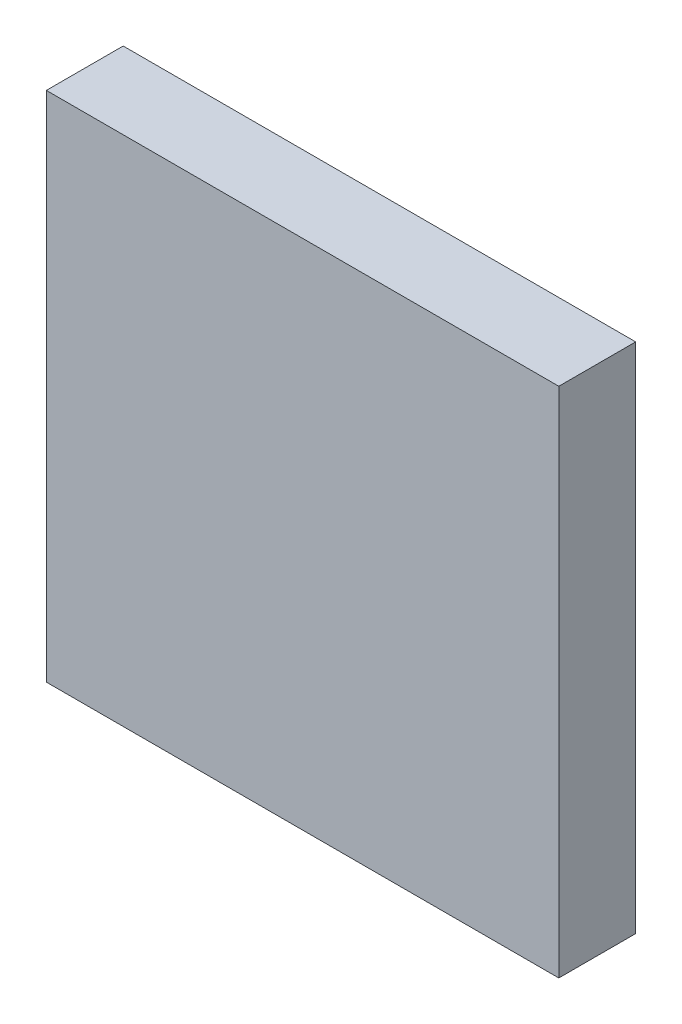
SolidWorks part; units mm, degrees
ref_plane "前视基准面" through (0, 0, 0) normal (0, 0, 1) x (1, 0, 0)
ref_plane "上视基准面" through (0, 0, 0) normal (0, 1, 0) x (1, 0, 0)
ref_plane "右视基准面" through (0, 0, 0) normal (1, 0, 0) x (0, 0, -1)
sketch "草图1" plane through (0, 0, 0) normal (0, 0, 1) x (1, 0, 0)
  line L1 (0, 0) -> (40, 0)
  line L2 (0, 0) -> (0, 40)
  line L3 (0, 40) -> (40, 40)
  line L4 (40, 0) -> (40, 40)
  dimension "D1" = 40
  dimension "D2" = 40
extrude "凸台-拉伸1" add sketch "草图1" along normal blind 6
